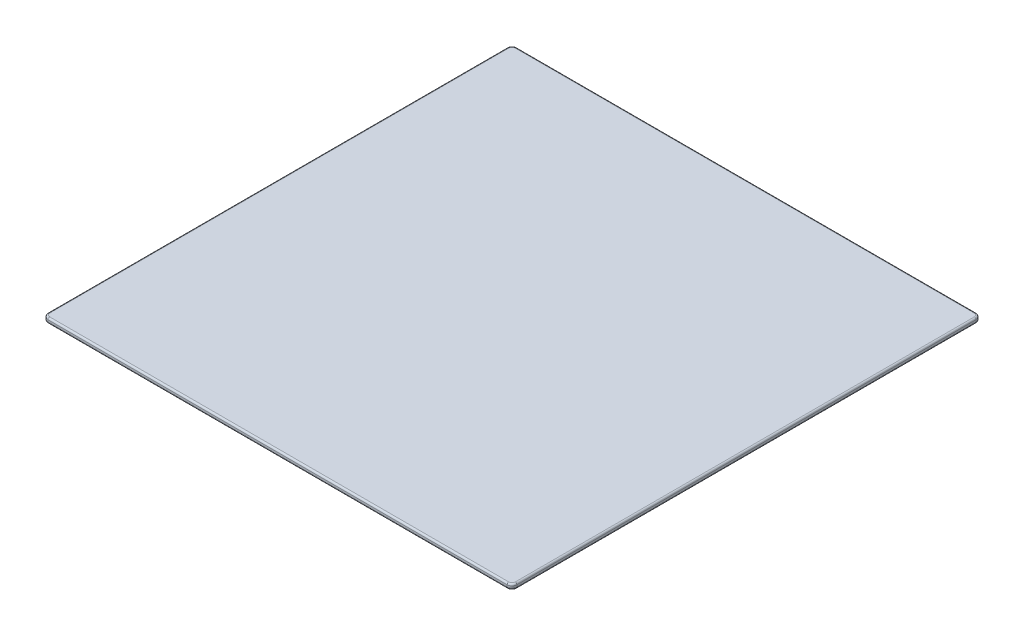
SolidWorks part; units mm, degrees
ref_plane "Front Plane" through (0, 0, 0) normal (0, 0, 1) x (1, 0, 0)
ref_plane "Top Plane" through (0, 0, 0) normal (0, 1, 0) x (1, 0, 0)
ref_plane "Right Plane" through (0, 0, 0) normal (1, 0, 0) x (0, 0, -1)
sketch "Sketch2" plane through (0, 0, 0) normal (0, 1, 0) x (1, 0, 0)
  line L1 (-142.875, -142.875) -> (142.875, -142.875)
  line L2 (-142.875, -142.875) -> (-142.875, 142.875)
  line L3 (-142.875, 142.875) -> (142.875, 142.875)
  line L4 (142.875, -142.875) -> (142.875, 142.875)
  line L5 (-142.875, -142.875) -> (142.875, 142.875) construction
  line L6 (-142.875, 142.875) -> (142.875, -142.875) construction
  point P0 (0, 0)
  dimension "D1" = 285.75
  dimension "D2" = 285.75
extrude "Boss-Extrude1" add sketch "Sketch2" along normal blind 3.175
fillet "Fillet1" radius 3 4 edges at (142.875, 1.5875, -142.875) (142.875, 1.5875, 142.875) (-142.875, 1.5875, 142.875) (-142.875, 1.5875, -142.875)
fillet "Fillet2" radius 1 8 edges at (-141.9963, 3.175, -141.9963) (0, 3.175, -142.875) (141.9963, 3.175, -141.9963) (142.875, 3.175, 0) (141.9963, 3.175, 141.9963) (0, 3.175, 142.875) (-141.9963, 3.175, 141.9963) (-142.875, 3.175, 0)
fillet "Fillet3" radius 1 8 edges at (-141.9963, 0, -141.9963) (-142.875, 0, 0) (-141.9963, 0, 141.9963) (0, 0, 142.875) (141.9963, 0, 141.9963) (142.875, 0, 0) (141.9963, 0, -141.9963) (0, 0, -142.875)
